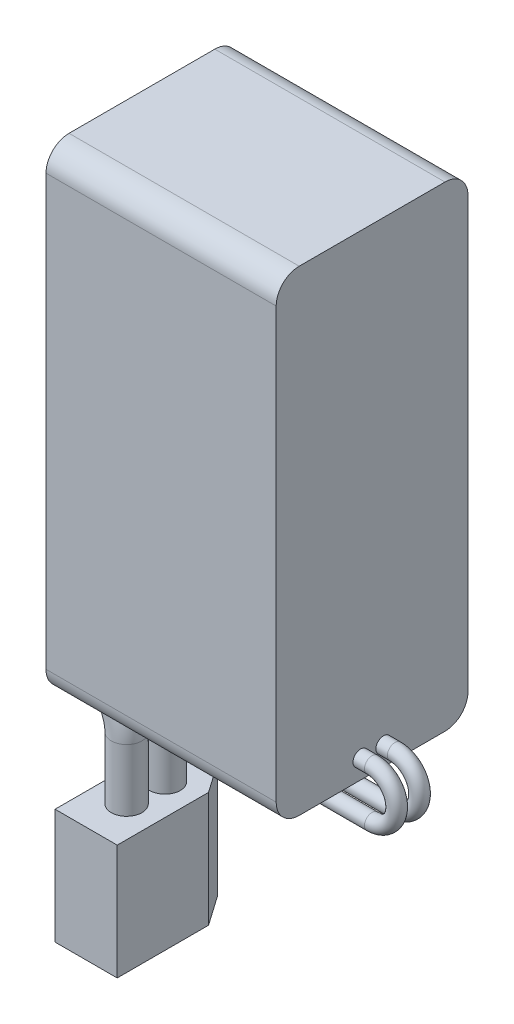
SolidWorks part; units mm, degrees
ref_plane "Front Plane" through (0, 0, 0) normal (1, 0, 0) x (0, 1, 0)
ref_plane "Top Plane" through (0, 0, 0) normal (0, 0, 1) x (0, 1, 0)
ref_plane "Right Plane" through (0, 0, 0) normal (0, 1, 0) x (-1, 0, 0)
sketch "Sketch1" plane through (0, 0, 0) normal (0, 0, 1) x (0, 1, 0)
  line L1 (-31, -15) -> (31, -15)
  line L2 (-31, -15) -> (-31, 15)
  line L3 (-31, 15) -> (31, 15)
  line L4 (31, -15) -> (31, 15)
  line L5 (-31, -15) -> (31, 15) construction
  line L6 (-31, 15) -> (31, -15) construction
  point P0 (0, 0)
  dimension "D1" = 62
  dimension "D2" = 30
extrude "Boss-Extrude1" add sketch "Sketch1" along normal blind 25
fillet "Fillet1" radius 3 4 edges at (0, -31, 0) (0, -31, 25) (0, 31, 0) (0, 31, 25)
sketch "Sketch2" plane through (-15, 0, 10) normal (1, 0, 0) x (0, 0, -1)
  line L0 (0, -28) -> (-5, -28) construction
  line L2 (-2.5, -28) -> (-2.5, -20.0823) construction
  line L3 (10, 28) -> (10, -28) construction
  line L4 (-15, 28) -> (-15, -28) construction
  line L5 (10, 28) -> (10, -28) construction
  line L6 (-15, 28) -> (-15, -28) construction
  line L7 (-12, -31) -> (7, -31) construction
  circle A0 centre (0, -28) radius 2
  circle A1 centre (-5, -28) radius 2
  dimension "D1" = 4
  dimension "D2" = 5
  dimension "D3" = 3
sketch "Sketch4" plane through (0, 0, 0) normal (0, 0, 1) x (0, 1, 0)
  line L0 (-28, 15) -> (-28, 17.6418)
  line L1 (-39.8327, 14.4947) -> (-47.9299, 14.4947)
  arc A0 (-28, 17.6418) -> (-33.9722, 18.6551) centre (-31.072, 17.6418) ccw
  arc A1 (-33.9722, 18.6551) -> (-39.8327, 14.4947) centre (-39.8327, 20.7027) cw
sweep "Sweep2" add profiles "Sketch2" path "Sketch4"
sketch "Sketch5" plane through (15, 0, 0) normal (1, 0, 0) x (0, 1, 0)
  line L0 (-28.5, 13.9916) -> (-28.5, 11.0084) construction
  line L1 (-28, 0) -> (28, 0) construction
  line L2 (-28, 25) -> (28, 25) construction
  line L3 (-28, 0) -> (28, 0) construction
  line L4 (-28, 25) -> (28, 25) construction
  line L5 (-28.5, 12.5) -> (-24.2481, 12.5) construction
  line L6 (-31, 22) -> (-31, 3) construction
  circle A0 centre (-28.5, 13.9916) radius 1
  circle A1 centre (-28.5, 11.0084) radius 1
  dimension "D1" = 2
  dimension "D2" = 2.5
sketch "Sketch6" plane through (0, 0, 0) normal (0, 0, 1) x (0, 1, 0)
  line L0 (-28.5, -16.4977) -> (-28.5, -15)
  line L1 (-34.9001, -16.4977) -> (-34.9001, 6.4232)
  arc A0 (-28.5, -16.4977) -> (-34.9001, -16.4977) centre (-31.7, -16.4977) cw
sweep "Sweep3" add profiles "Sketch5" path "Sketch6"
sketch "Sketch7" plane through (-6.4232, 0, 0) normal (-1, 0, 0) x (0, -1, 0)
  line L0 (34.9001, 12.5) -> (35.3785, 12.5) construction
  line L1 (33.4001, 9.5) -> (36.4001, 9.5)
  line L2 (33.4001, 9.5) -> (33.4001, 15.5)
  line L3 (33.4001, 15.5) -> (36.4001, 15.5)
  line L4 (36.4001, 9.5) -> (36.4001, 15.5)
  line L5 (33.4001, 9.5) -> (36.4001, 15.5) construction
  line L6 (33.4001, 15.5) -> (36.4001, 9.5) construction
  circle A0 centre (34.9001, 11.0084) radius 1 construction
  circle A1 centre (34.9001, 13.9916) radius 1 construction
  circle A2 centre (34.9001, 11.0084) radius 1 construction
  circle A3 centre (34.9001, 13.9916) radius 1 construction
  point P0 (34.9001, 12.5)
  dimension "D1" = 6
  dimension "D2" = 3
extrude "Boss-Extrude2" add sketch "Sketch7" along normal blind 3.5 draft 3
sketch "Sketch8" plane through (0, -47.9299, 0) normal (0, -1, 0) x (1, 0, 0)
  line L0 (-18.5447, 8.3691) -> (-15.8888, 4.576)
  line L1 (-15.8888, 4.576) -> (-13.1007, 4.576)
  line L2 (-18.5447, 8.3691) -> (-18.5447, 20.276)
  line L3 (-18.5447, 20.276) -> (-10.4447, 20.276)
  line L4 (-10.4447, 8.3691) -> (-10.4447, 20.276)
  line L5 (-18.5447, 4.576) -> (-10.4447, 20.276) construction
  line L6 (-18.5447, 20.276) -> (-10.4447, 4.576) construction
  line L7 (-13.1007, 4.576) -> (-10.4447, 8.3691)
  circle A0 centre (-14.4947, 10) radius 2 construction
  circle A1 centre (-14.4947, 15) radius 2 construction
  circle A2 centre (-14.4947, 10) radius 2 construction
  circle A3 centre (-14.4947, 15) radius 2 construction
  point P0 (-14.4947, 12.426)
  dimension "D1" = 35
  dimension "D2" = 15.7
  dimension "D3" = 8.1
extrude "Boss-Extrude3" add sketch "Sketch8" along normal blind 15
